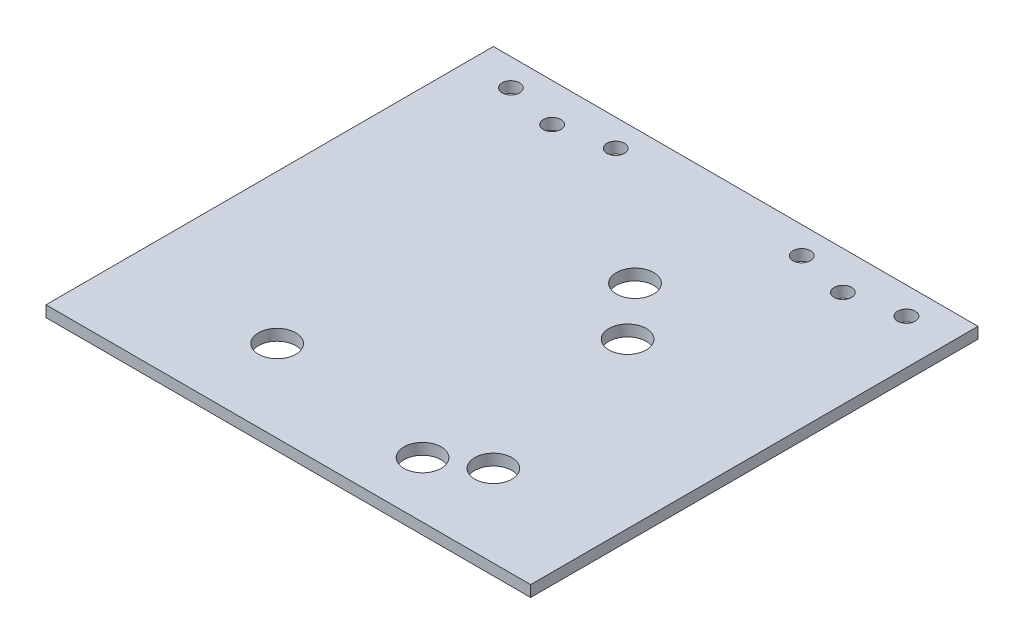
SolidWorks part; units mm, degrees
ref_plane "Front Plane" through (0, 0, 0) normal (0, 0, 1) x (1, 0, 0)
ref_plane "Top Plane" through (0, 0, 0) normal (0, 1, 0) x (1, 0, 0)
ref_plane "Right Plane" through (0, 0, 0) normal (1, 0, 0) x (0, 0, -1)
sketch "Sketch1" plane through (0, 0, 0) normal (0, 1, 0) x (1, 0, 0)
  line L1 (0, 0) -> (130, 0)
  line L2 (0, 0) -> (0, -150)
  line L3 (0, -150) -> (130, -150)
  line L4 (130, 0) -> (130, -150)
  dimension "D1" = 130
  dimension "D2" = 150
extrude "Boss-Extrude1" add sketch "Sketch1" along normal blind 3
hole_wizard "Ø10.0 (10) Diameter Hole2" positions "Sketch3" profile "Sketch2" hole size "Ø10.0" standard "ANSI Metric" end condition through all
sketch "Sketch3" plane through (0, 3, 0) normal (0, 1, 0) x (1, 0, 0)
  point P16 (40, -128)
  point P18 (98, -128)
  point P20 (74, -66)
sketch "Sketch2" plane through (40, 3, 128) normal (1, 0, 0) x (0, 0, 1)
  line L0 (0, 0) -> (0, 3)
  line L1 (0, 3) -> (5, 3)
  line L2 (5, 3) -> (5, 0)
  line L5 (5, 0) -> (0, 0)
  line L11 (0, -6.35) -> (0, 107.95) construction
  dimension "Thru Hole Dia." = 10
  dimension "Thru Hole Depth" = 3
sketch "Sketch4" plane through (0, 0, 0) normal (0, 1, 0) x (1, 0, 0)
  line L0 (4.6863, -27.3137) -> (27.3137, -4.6863) construction
  line L1 (4.6863, -4.6863) -> (27.3137, -4.6863) construction
  line L2 (4.6863, -4.6863) -> (4.6863, -27.3137) construction
  line L3 (4.6863, -27.3137) -> (27.3137, -27.3137) construction
  line L4 (27.3137, -4.6863) -> (27.3137, -27.3137) construction
  line L5 (4.6863, -4.6863) -> (27.3137, -27.3137) construction
  line L6 (130, 0) -> (0, 0) construction
  line L7 (0, 0) -> (0, -150) construction
  line L8 (130, -150) -> (130, 0) construction
  line L9 (102.6863, -4.6863) -> (125.3137, -4.6863) construction
  line L10 (102.6863, -4.6863) -> (102.6863, -27.3137) construction
  line L11 (102.6863, -27.3137) -> (125.3137, -27.3137) construction
  line L12 (125.3137, -4.6863) -> (125.3137, -27.3137) construction
  line L13 (102.6863, -4.6863) -> (125.3137, -27.3137) construction
  line L14 (102.6863, -27.3137) -> (125.3137, -4.6863) construction
  line L15 (16, -16) -> (114, -16) construction
  line L17 (53.6863, -4.6863) -> (76.3137, -4.6863) construction
  line L18 (53.6863, -4.6863) -> (53.6863, -27.3137) construction
  line L19 (53.6863, -27.3137) -> (76.3137, -27.3137) construction
  line L20 (76.3137, -4.6863) -> (76.3137, -27.3137) construction
  line L21 (53.6863, -4.6863) -> (76.3137, -27.3137) construction
  line L22 (53.6863, -27.3137) -> (76.3137, -4.6863) construction
  circle A0 centre (16, -16) radius 16 construction
  circle A1 centre (65, -16) radius 16 construction
  circle A2 centre (114, -16) radius 16 construction
  point P10 (114, -16)
  dimension "D2" = 32
  dimension "D3" = 32
  dimension "D1" = 32
hole_wizard "Ø14.0 (14) Diameter Hole1" positions "Sketch6" profile "Sketch5" hole size "Ø14.0" standard "ANSI Metric" end condition through all
sketch "Sketch6" plane through (0, 3, 0) normal (0, 1, 0) x (1, 0, 0)
  point P0 (16, -16)
  point P2 (114, -16)
sketch "Sketch5" plane through (16, 3, 16) normal (1, 0, 0) x (0, 0, 1)
  line L0 (0, 0) -> (0, 3)
  line L1 (0, 3) -> (7, 3)
  line L2 (7, 3) -> (7, 0)
  line L5 (7, 0) -> (0, 0)
  line L11 (0, -6.35) -> (0, 107.95) construction
  dimension "Thru Hole Dia." = 14
  dimension "Thru Hole Depth" = 3
hole_wizard "Ø5.0 (5) Diameter Hole1" positions "Sketch8" profile "Sketch7" hole size "Ø5.0" standard "ANSI Metric" end condition through all
sketch "Sketch8" plane through (0, 3, 0) normal (0, 1, 0) x (1, 0, 0)
  point P0 (4.6863, -27.3137)
  point P2 (4.6863, -4.6863)
  point P4 (27.3137, -4.6863)
  point P6 (27.3137, -27.3137)
  point P8 (102.6863, -27.3137)
  point P10 (125.3137, -27.3137)
  point P12 (125.3137, -4.6863)
  point P14 (102.6863, -4.6863)
sketch "Sketch7" plane through (4.6863, 3, 27.3137) normal (1, 0, 0) x (0, 0, 1)
  line L0 (0, 0) -> (0, 3)
  line L1 (0, 3) -> (2.5, 3)
  line L2 (2.5, 3) -> (2.5, 0)
  line L5 (2.5, 0) -> (0, 0)
  line L11 (0, -6.35) -> (0, 107.95) construction
  dimension "Thru Hole Dia." = 5
  dimension "Thru Hole Depth" = 3
hole_wizard "Ø10.0 (10) Diameter Hole1" positions "Sketch10" profile "Sketch9" hole size "Ø10.0" standard "ANSI Metric" end condition through all
sketch "Sketch10" plane through (0, 3, 0) normal (0, 1, 0) x (1, 0, 0)
  point P12 (86, -135)
  point P15 (86, -80)
sketch "Sketch9" plane through (86, 3, 135) normal (1, 0, 0) x (0, 0, 1)
  line L0 (0, 0) -> (0, 3)
  line L1 (0, 3) -> (5, 3)
  line L2 (5, 3) -> (5, 0)
  line L5 (5, 0) -> (0, 0)
  line L11 (0, -6.35) -> (0, 107.95) construction
  dimension "Thru Hole Dia." = 10
  dimension "Thru Hole Depth" = 3
hole_wizard "Ø9.0 (9) Diameter Hole1" positions "Sketch12" profile "Sketch11" hole size "Ø9.0" standard "ANSI Metric" end condition through all
sketch "Sketch12" plane through (0, 3, 0) normal (0, 1, 0) x (1, 0, 0)
  point P5 (65, -16)
sketch "Sketch11" plane through (65, 3, 16) normal (1, 0, 0) x (0, 0, 1)
  line L0 (0, 0) -> (0, 3)
  line L1 (0, 3) -> (4.5, 3)
  line L2 (4.5, 3) -> (4.5, 0)
  line L5 (4.5, 0) -> (0, 0)
  line L11 (0, -6.35) -> (0, 107.95) construction
  dimension "Thru Hole Dia." = 9
  dimension "Thru Hole Depth" = 3
hole_wizard "Ø5.0 (5) Diameter Hole2" positions "Sketch14" profile "Sketch13" hole size "Ø5.0" standard "ANSI Metric" end condition through all
sketch "Sketch14" plane through (0, 3, 0) normal (0, 1, 0) x (1, 0, 0)
  point P0 (53.6863, -27.3137)
  point P2 (76.3137, -27.3137)
  point P4 (76.3137, -4.6863)
  point P6 (53.6863, -4.6863)
sketch "Sketch13" plane through (53.6863, 3, 27.3137) normal (1, 0, 0) x (0, 0, 1)
  line L0 (0, 0) -> (0, 3)
  line L1 (0, 3) -> (2.5, 3)
  line L2 (2.5, 3) -> (2.5, 0)
  line L5 (2.5, 0) -> (0, 0)
  line L11 (0, -6.35) -> (0, 107.95) construction
  dimension "Thru Hole Dia." = 5
  dimension "Thru Hole Depth" = 3
sketch "Sketch15" plane through (0, 0, 0) normal (0, 1, 0) x (1, 0, 0)
  line L0 (130, -150) -> (130, 0) construction
  line L1 (0, 0) -> (130, 0)
  line L2 (0, 0) -> (0, -30)
  line L3 (0, -30) -> (130, -30)
  line L4 (130, 0) -> (130, -30)
  line L5 (0, -150) -> (130, -150) construction
  dimension "D1" = 120
extrude "Cut-Extrude1" cut sketch "Sketch15" along normal through all
sketch "Sketch16" plane through (0, 0, 0) normal (0, 1, 0) x (1, 0, 0)
  line L0 (104, -40.25) -> (104, -37.25) construction
  line L1 (118.05, -37.25) -> (89.95, -37.25) construction
  line L2 (0, -30) -> (130, -30) construction
  line L3 (130, -150) -> (130, -30) construction
  line L4 (26, -40.25) -> (26, -37.25) construction
  line L5 (40.05, -37.25) -> (11.95, -37.25) construction
  circle A0 centre (89.95, -37.25) radius 2.35
  circle A1 centre (118.05, -37.25) radius 2.35
  circle A2 centre (104, -40.25) radius 2.35
  circle A3 centre (11.95, -37.25) radius 2.35
  circle A4 centre (40.05, -37.25) radius 2.35
  circle A5 centre (26, -40.25) radius 2.35
  dimension "D4" = 4.7
  dimension "D1" = 28.1
  dimension "D2" = 10.25
  dimension "D3" = 3
  dimension "D5" = 26
  dimension "D6" = 28.1
  dimension "D7" = 78
extrude "Cut-Extrude2" cut sketch "Sketch16" along normal through all
equation "\"a\"= 130"
equation "\"b\"= 150"
equation "\"D2@Sketch1\"=\"b\""
equation "\"D1@Sketch1\"=\"a\""
